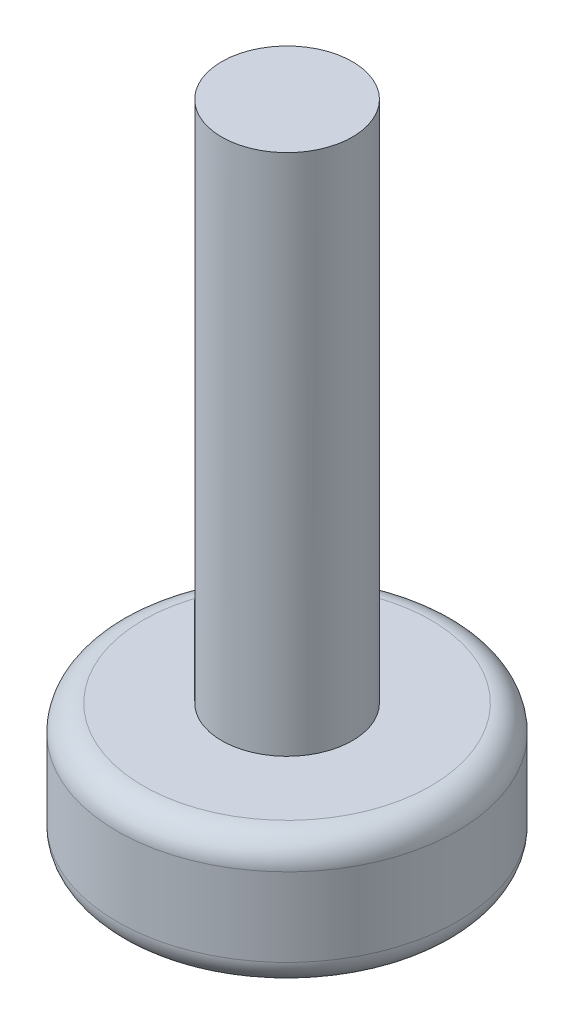
SolidWorks part; units mm, degrees
material "Plain Carbon Steel"
ref_plane "Front Plane" through (0, 0, 0) normal (0, 0, 1) x (1, 0, 0)
ref_plane "Top Plane" through (0, 0, 0) normal (0, 1, 0) x (1, 0, 0)
ref_plane "Right Plane" through (0, 0, 0) normal (1, 0, 0) x (0, 0, -1)
sketch "Sketch1" plane through (0, 0, 0) normal (0, 1, 0) x (1, 0, 0)
  circle A0 centre (0, 0) radius 2.5
  dimension "D1" = 5
extrude "Boss-Extrude1" add sketch "Sketch1" along normal blind 20
cosmetic thread "Cosmetic Thread1" parameters "D1"=30, "D2"=0.3
sketch "Sketch2" plane through (0, 0, 0) normal (0, 0, 1) x (1, 0, 0)
  line L0 (0, 0) -> (0, -5)
  line L1 (-5.5, 0) -> (0, 0)
  line L2 (-6.5, -1) -> (-6.5, -4)
  line L3 (-5.5, -5) -> (0, -5)
  arc A2 (-6.5, -4) -> (-5.5, -5) centre (-5.5, -4) ccw
  arc A3 (-5.5, 0) -> (-6.5, -1) centre (-5.5, -1) ccw
  point P9 (6.5, -5)
  point P12 (-6.5, -5)
  point P15 (-6.5, 0)
  dimension "D1" = 13
  dimension "D2" = 6.5
  dimension "D3" = 5
  dimension "D4" = 0
revolve "Revolve1" add sketch "Sketch2" angle 360 about L0
